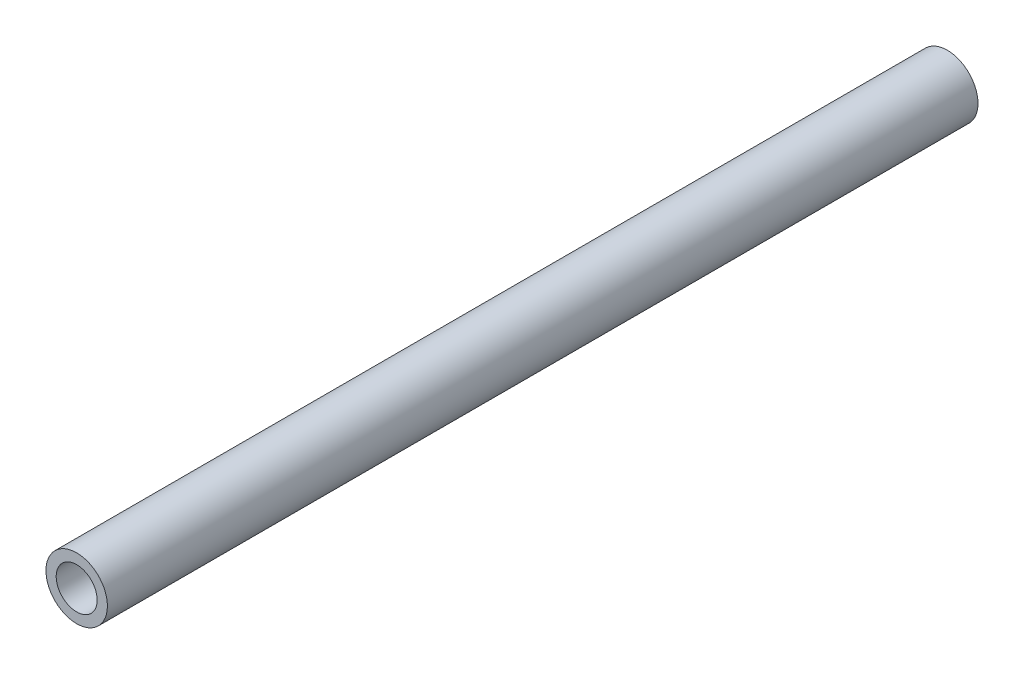
SolidWorks part; units mm, degrees
material "Rubber"
ref_plane "Front Plane" through (0, 0, 0) normal (0, 0, 1) x (1, 0, 0)
ref_plane "Top Plane" through (0, 0, 0) normal (0, 1, 0) x (1, 0, 0)
ref_plane "Right Plane" through (0, 0, 0) normal (1, 0, 0) x (0, 0, -1)
sketch "Sketch1" plane through (0, 0, 0) normal (0, 0, 1) x (1, 0, 0)
  circle A0 centre (0, 0) radius 19.05
extrude "Boss-Extrude1" add sketch "Sketch1" along normal blind 539.75
sketch "Sketch2" plane through (0, 0, 539.75) normal (0, 0, 1) x (1, 0, 0)
  circle A0 centre (0, 0) radius 12.7
extrude "Cut-Extrude1" cut sketch "Sketch2" against normal blind 539.75
